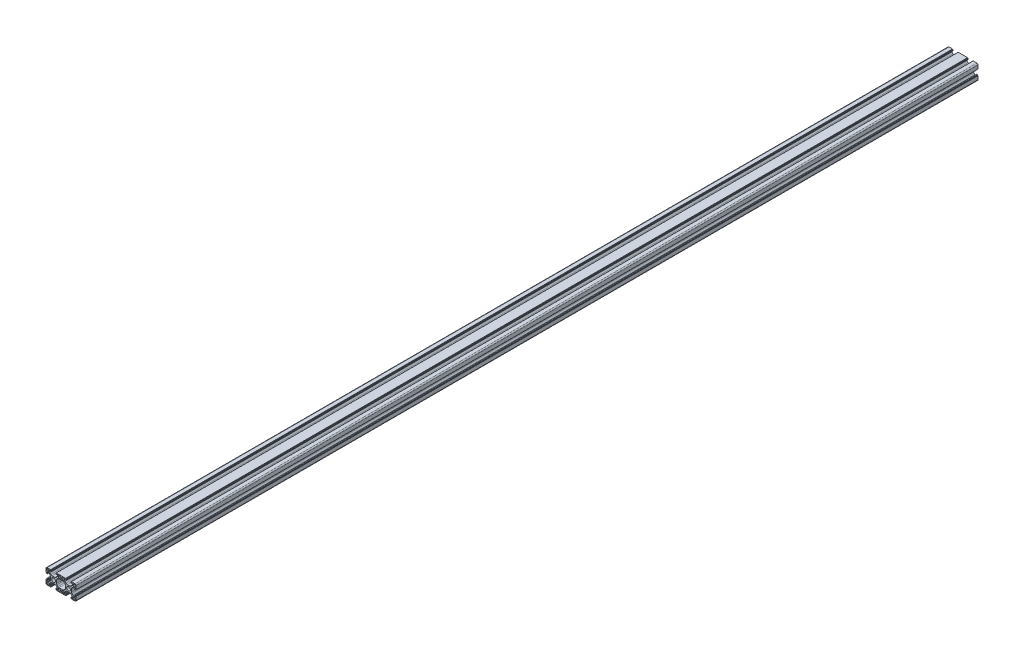
SolidWorks part; units mm, degrees
ref_plane "Спереди" through (0, 0, 0) normal (0, 0, 1) x (1, 0, 0)
ref_plane "Сверху" through (0, 0, 0) normal (0, 1, 0) x (1, 0, 0)
ref_plane "Справа" through (0, 0, 0) normal (1, 0, 0) x (0, 0, -1)
sketch "Эскиз2" plane through (0, 0, 0) normal (0, 0, 1) x (1, 0, 0)
  line L0 (-3.2929, 8.1556) -> (-1.7929, 6.6556) construction
  line L1 (18.2071, 9.6556) -> (15.2071, 6.6556) construction
  line L2 (-10.8929, 0.5556) -> (-0.8929, 10.5556) construction
  line L3 (9.1071, 4.5556) -> (11.0059, 4.5556)
  line L4 (9.1071, 0.5556) -> (19.1071, 10.5556) construction
  line L5 (16.7071, 8.1556) -> (15.2071, 9.6556) construction
  line L6 (12.4201, 5.1414) -> (13.7213, 6.4426)
  line L7 (16.0071, 6.6556) -> (17.4071, 6.6556)
  line L8 (15.2071, 7.4556) -> (15.2071, 8.8556)
  line L9 (17.4071, 9.6556) -> (16.0071, 9.6556)
  line L10 (14.3071, 8.7556) -> (14.3071, 7.8568)
  line L11 (12.8704, 8.6288) -> (13.3507, 9.1091)
  line L12 (12.3071, 10.1047) -> (12.8071, 10.1047)
  line L13 (12.6936, 8.5556) -> (12.4071, 8.5556)
  line L14 (13.7042, 9.2556) -> (13.8071, 9.2556)
  line L15 (12.8071, 10.4056) -> (12.8071, 10.1047)
  line L16 (12.1571, 9.9547) -> (12.1571, 8.8056)
  line L17 (17.6071, 10.5556) -> (12.9571, 10.5556)
  line L18 (18.2071, 8.8556) -> (18.2071, 7.4556)
  line L19 (19.1071, 9.0556) -> (19.1071, 4.4056)
  line L20 (18.5062, 3.6056) -> (17.3571, 3.6056)
  line L21 (18.9571, 4.2556) -> (18.6562, 4.2556)
  line L22 (17.8071, 5.1527) -> (17.8071, 5.2556)
  line L23 (17.1071, 4.142) -> (17.1071, 3.8556)
  line L24 (18.6562, 3.7556) -> (18.6562, 4.2556)
  line L25 (17.1804, 4.3188) -> (17.6607, 4.7991)
  line L26 (17.3071, 5.7556) -> (16.4083, 5.7556)
  line L27 (13.6929, 3.8686) -> (14.9941, 5.1698)
  line L28 (13.1071, 0.5556) -> (13.1071, 2.4544)
  line L29 (13.1071, 0.5556) -> (13.1071, -1.3432)
  line L30 (13.6929, -2.7574) -> (14.9941, -4.0586)
  line L31 (15.2071, -6.3444) -> (15.2071, -7.7444)
  line L32 (16.0071, -5.5444) -> (17.4071, -5.5444)
  line L33 (18.2071, -7.7444) -> (18.2071, -6.3444)
  line L34 (17.3071, -4.6444) -> (16.4083, -4.6444)
  line L35 (17.1804, -3.2076) -> (17.6607, -3.688)
  line L36 (18.6562, -2.6444) -> (18.6562, -3.1444)
  line L37 (17.1071, -3.0309) -> (17.1071, -2.7444)
  line L38 (17.8071, -4.0415) -> (17.8071, -4.1444)
  line L39 (18.9571, -3.1444) -> (18.6562, -3.1444)
  line L40 (18.5062, -2.4944) -> (17.3571, -2.4944)
  line L41 (19.1071, -7.9444) -> (19.1071, -3.2944)
  line L42 (17.4071, -8.5444) -> (16.0071, -8.5444)
  line L43 (17.6071, -9.4444) -> (12.9571, -9.4444)
  line L44 (12.1571, -8.8435) -> (12.1571, -7.6944)
  line L45 (12.8071, -9.2944) -> (12.8071, -8.9935)
  line L46 (13.7042, -8.1444) -> (13.8071, -8.1444)
  line L47 (12.6936, -7.4444) -> (12.4071, -7.4444)
  line L48 (12.3071, -8.9935) -> (12.8071, -8.9935)
  line L49 (12.8704, -7.5176) -> (13.3507, -7.998)
  line L50 (14.3071, -7.6444) -> (14.3071, -6.7456)
  line L51 (12.4201, -4.0302) -> (13.7213, -5.3314)
  line L52 (9.1071, -3.4444) -> (11.0059, -3.4444)
  line L53 (18.2071, -8.5444) -> (15.2071, -5.5444) construction
  line L54 (9.1071, 0.5556) -> (19.1071, -9.4444) construction
  line L55 (16.7071, -7.0444) -> (18.2071, -5.5444) construction
  line L56 (9.1071, -3.4444) -> (7.2083, -3.4444)
  line L57 (5.7941, -4.0302) -> (4.4929, -5.3314)
  line L58 (2.2071, -5.5444) -> (0.8071, -5.5444)
  line L59 (3.0071, -6.3444) -> (3.0071, -7.7444)
  line L60 (0.8071, -8.5444) -> (2.2071, -8.5444)
  line L61 (3.9071, -7.6444) -> (3.9071, -6.7456)
  line L62 (5.3439, -7.5176) -> (4.8636, -7.998)
  line L63 (5.9071, -8.9935) -> (5.4071, -8.9935)
  line L64 (5.5207, -7.4444) -> (5.8071, -7.4444)
  line L65 (4.51, -8.1444) -> (4.4071, -8.1444)
  line L66 (5.4071, -9.2944) -> (5.4071, -8.9935)
  line L67 (6.0571, -8.8435) -> (6.0571, -7.6944)
  line L68 (0.6071, -9.4444) -> (5.2571, -9.4444)
  line L69 (0.0071, -7.7444) -> (0.0071, -6.3444)
  line L70 (0.9071, -4.6444) -> (1.8059, -4.6444)
  line L71 (4.5213, -2.7574) -> (3.2201, -4.0586)
  line L72 (5.1071, 0.5556) -> (5.1071, -1.3432)
  line L73 (-1.7929, 9.6556) -> (-4.7929, 6.6556) construction
  line L74 (0.0071, -8.5444) -> (3.0071, -5.5444) construction
  line L75 (-3.2929, -7.0444) -> (-4.7929, -8.5444) construction
  line L76 (9.1071, 0.5556) -> (-0.8929, -9.4444) construction
  line L77 (1.5071, -7.0444) -> (3.0071, -8.5444) construction
  line L78 (5.1071, 0.5556) -> (5.1071, 2.4544)
  line L79 (4.5213, 3.8686) -> (3.2201, 5.1698)
  line L80 (3.0071, 7.4556) -> (3.0071, 8.8556)
  line L81 (2.2071, 6.6556) -> (0.8071, 6.6556)
  line L82 (0.0071, 8.8556) -> (0.0071, 7.4556)
  line L83 (0.9071, 5.7556) -> (1.8059, 5.7556)
  line L84 (0.8071, 9.6556) -> (2.2071, 9.6556)
  line L85 (0.6071, 10.5556) -> (5.2571, 10.5556)
  line L86 (6.0571, 9.9547) -> (6.0571, 8.8056)
  line L87 (5.4071, 10.4056) -> (5.4071, 10.1047)
  line L88 (4.51, 9.2556) -> (4.4071, 9.2556)
  line L89 (5.5207, 8.5556) -> (5.8071, 8.5556)
  line L90 (5.9071, 10.1047) -> (5.4071, 10.1047)
  line L91 (5.3439, 8.6288) -> (4.8636, 9.1091)
  line L92 (3.9071, 8.7556) -> (3.9071, 7.8568)
  line L93 (5.7941, 5.1414) -> (4.4929, 6.4426)
  line L94 (9.1071, 4.5556) -> (7.2083, 4.5556)
  line L95 (-2.6569, 0.5556) -> (20.6115, 0.5556) construction
  line L96 (0.0071, 9.6556) -> (3.0071, 6.6556) construction
  line L97 (9.1071, -11.5308) -> (9.1071, 11.2745) construction
  line L98 (9.1071, 0.5556) -> (-0.8929, 10.5556) construction
  line L99 (1.5071, 8.1556) -> (0.0071, 6.6556) construction
  line L100 (-10.8929, 0.5556) -> (-0.8929, -9.4444) construction
  line L101 (-1.7929, -8.5444) -> (-4.7929, -5.5444) construction
  line L102 (-18.4929, -7.0444) -> (-19.9929, -5.5444) construction
  line L103 (-10.8929, 0.5556) -> (-20.8929, -9.4444) construction
  line L104 (-19.9929, -8.5444) -> (-16.9929, -5.5444) construction
  line L105 (-18.4929, 8.1556) -> (-16.9929, 9.6556) construction
  line L106 (-10.8929, 0.5556) -> (-20.8929, 10.5556) construction
  line L107 (-19.9929, 9.6556) -> (-16.9929, 6.6556) construction
  line L108 (-10.8929, 4.5556) -> (-8.9941, 4.5556)
  line L109 (-7.5799, 5.1414) -> (-6.2787, 6.4426)
  line L110 (-5.6929, 8.7556) -> (-5.6929, 7.8568)
  line L111 (-7.1296, 8.6288) -> (-6.6493, 9.1091)
  line L112 (-7.6929, 10.1047) -> (-7.1929, 10.1047)
  line L113 (-7.3064, 8.5556) -> (-7.5929, 8.5556)
  line L114 (-6.2958, 9.2556) -> (-6.1929, 9.2556)
  line L115 (-7.1929, 10.4056) -> (-7.1929, 10.1047)
  line L116 (-7.8429, 9.9547) -> (-7.8429, 8.8056)
  line L117 (-2.3929, 10.5556) -> (-7.0429, 10.5556)
  line L118 (-2.5929, 9.6556) -> (-3.9929, 9.6556)
  line L119 (-2.6929, 5.7556) -> (-3.5917, 5.7556)
  line L120 (-1.7929, 8.8556) -> (-1.7929, 7.4556)
  line L121 (-3.9929, 6.6556) -> (-2.5929, 6.6556)
  line L122 (-4.7929, 7.4556) -> (-4.7929, 8.8556)
  line L123 (-6.3071, 3.8686) -> (-5.0059, 5.1698)
  line L124 (-6.8929, 0.5556) -> (-6.8929, 2.4544)
  line L125 (-6.8929, 0.5556) -> (-6.8929, -1.3432)
  line L126 (-6.3071, -2.7574) -> (-5.0059, -4.0586)
  line L127 (-2.6929, -4.6444) -> (-3.5917, -4.6444)
  line L128 (-1.7929, -7.7444) -> (-1.7929, -6.3444)
  line L129 (-2.3929, -9.4444) -> (-7.0429, -9.4444)
  line L130 (-7.8429, -8.8435) -> (-7.8429, -7.6944)
  line L131 (-7.1929, -9.2944) -> (-7.1929, -8.9935)
  line L132 (-6.2958, -8.1444) -> (-6.1929, -8.1444)
  line L133 (-7.3064, -7.4444) -> (-7.5929, -7.4444)
  line L134 (-7.6929, -8.9935) -> (-7.1929, -8.9935)
  line L135 (-7.1296, -7.5176) -> (-6.6493, -7.998)
  line L136 (-5.6929, -7.6444) -> (-5.6929, -6.7456)
  line L137 (-2.5929, -8.5444) -> (-3.9929, -8.5444)
  line L138 (-4.7929, -6.3444) -> (-4.7929, -7.7444)
  line L139 (-3.9929, -5.5444) -> (-2.5929, -5.5444)
  line L140 (-7.5799, -4.0302) -> (-6.2787, -5.3314)
  line L141 (-10.8929, -3.4444) -> (-8.9941, -3.4444)
  line L142 (-10.8929, -3.4444) -> (-12.7917, -3.4444)
  line L143 (-14.2059, -4.0302) -> (-15.5071, -5.3314)
  line L144 (-16.0929, -7.6444) -> (-16.0929, -6.7456)
  line L145 (-14.6561, -7.5176) -> (-15.1364, -7.998)
  line L146 (-14.0929, -8.9935) -> (-14.5929, -8.9935)
  line L147 (-14.4793, -7.4444) -> (-14.1929, -7.4444)
  line L148 (-15.49, -8.1444) -> (-15.5929, -8.1444)
  line L149 (-14.5929, -9.2944) -> (-14.5929, -8.9935)
  line L150 (-13.9429, -8.8435) -> (-13.9429, -7.6944)
  line L151 (-19.3929, -9.4444) -> (-14.7429, -9.4444)
  line L152 (-19.1929, -8.5444) -> (-17.7929, -8.5444)
  line L153 (-20.8929, -7.9444) -> (-20.8929, -3.2944)
  line L154 (-20.2919, -2.4944) -> (-19.1429, -2.4944)
  line L155 (-20.7429, -3.1444) -> (-20.4419, -3.1444)
  line L156 (-19.5929, -4.0415) -> (-19.5929, -4.1444)
  line L157 (-18.8929, -3.0309) -> (-18.8929, -2.7444)
  line L158 (-20.4419, -2.6444) -> (-20.4419, -3.1444)
  line L159 (-18.9661, -3.2076) -> (-19.4464, -3.688)
  line L160 (-19.0929, -4.6444) -> (-18.1941, -4.6444)
  line L161 (-19.9929, -7.7444) -> (-19.9929, -6.3444)
  line L162 (-17.7929, -5.5444) -> (-19.1929, -5.5444)
  line L163 (-16.9929, -6.3444) -> (-16.9929, -7.7444)
  line L164 (-15.4787, -2.7574) -> (-16.7799, -4.0586)
  line L165 (-14.8929, 0.5556) -> (-14.8929, -1.3432)
  line L166 (-14.8929, 0.5556) -> (-14.8929, 2.4544)
  line L167 (-15.4787, 3.8686) -> (-16.7799, 5.1698)
  line L168 (-19.0929, 5.7556) -> (-18.1941, 5.7556)
  line L169 (-18.9661, 4.3188) -> (-19.4464, 4.7991)
  line L170 (-20.4419, 3.7556) -> (-20.4419, 4.2556)
  line L171 (-18.8929, 4.142) -> (-18.8929, 3.8556)
  line L172 (-19.5929, 5.1527) -> (-19.5929, 5.2556)
  line L173 (-20.7429, 4.2556) -> (-20.4419, 4.2556)
  line L174 (-20.2919, 3.6056) -> (-19.1429, 3.6056)
  line L175 (-20.8929, 9.0556) -> (-20.8929, 4.4056)
  line L176 (-19.9929, 8.8556) -> (-19.9929, 7.4556)
  line L177 (-19.3929, 10.5556) -> (-14.7429, 10.5556)
  line L178 (-13.9429, 9.9547) -> (-13.9429, 8.8056)
  line L179 (-14.5929, 10.4056) -> (-14.5929, 10.1047)
  line L180 (-15.49, 9.2556) -> (-15.5929, 9.2556)
  line L181 (-14.4793, 8.5556) -> (-14.1929, 8.5556)
  line L182 (-14.0929, 10.1047) -> (-14.5929, 10.1047)
  line L183 (-14.6561, 8.6288) -> (-15.1364, 9.1091)
  line L184 (-16.0929, 8.7556) -> (-16.0929, 7.8568)
  line L185 (-19.1929, 9.6556) -> (-17.7929, 9.6556)
  line L186 (-16.9929, 7.4556) -> (-16.9929, 8.8556)
  line L187 (-17.7929, 6.6556) -> (-19.1929, 6.6556)
  line L188 (-14.2059, 5.1414) -> (-15.5071, 6.4426)
  line L189 (-10.8929, 4.5556) -> (-12.7917, 4.5556)
  line L190 (-2.3929, -9.4444) -> (0.6071, -9.4444)
  line L191 (-2.6929, -4.6444) -> (0.9071, -4.6444)
  line L192 (-2.6929, 5.7556) -> (0.9071, 5.7556)
  line L193 (-2.3929, 10.5556) -> (0.6071, 10.5556)
  arc A0 (18.2071, 8.8556) -> (17.4071, 9.6556) centre (17.4071, 8.8556) ccw
  arc A1 (16.0071, 9.6556) -> (15.2071, 8.8556) centre (16.0071, 8.8556) ccw
  arc A2 (16.0071, 6.6556) -> (15.2071, 7.4556) centre (16.0071, 7.4556) cw
  arc A3 (17.6071, 10.5556) -> (19.1071, 9.0556) centre (17.6071, 9.0556) cw
  arc A4 (12.3071, 10.1047) -> (12.1571, 9.9547) centre (12.3071, 9.9547) ccw
  arc A5 (12.9571, 10.5556) -> (12.8071, 10.4056) centre (12.9571, 10.4056) ccw
  arc A6 (12.6936, 8.5556) -> (12.8704, 8.6288) centre (12.6936, 8.8056) ccw
  arc A7 (12.4071, 8.5556) -> (12.1571, 8.8056) centre (12.4071, 8.8056) cw
  arc A8 (13.3507, 9.1091) -> (13.7042, 9.2556) centre (13.7042, 8.7556) cw
  arc A9 (13.8071, 9.2556) -> (14.3071, 8.7556) centre (13.8071, 8.7556) cw
  arc A10 (11.6071, 0.5556) -> (9.1071, 3.0556) centre (9.1071, 0.5556) ccw
  arc A11 (11.0059, 4.5556) -> (12.4201, 5.1414) centre (11.0059, 6.5556) ccw
  arc A12 (14.3071, 7.8568) -> (13.7213, 6.4426) centre (12.3071, 7.8568) cw
  arc A13 (18.2071, 7.4556) -> (17.4071, 6.6556) centre (17.4071, 7.4556) cw
  arc A14 (17.8071, 5.2556) -> (17.3071, 5.7556) centre (17.3071, 5.2556) ccw
  arc A15 (17.6607, 4.7991) -> (17.8071, 5.1527) centre (17.3071, 5.1527) ccw
  arc A16 (17.1071, 3.8556) -> (17.3571, 3.6056) centre (17.3571, 3.8556) ccw
  arc A17 (17.1071, 4.142) -> (17.1804, 4.3188) centre (17.3571, 4.142) cw
  arc A18 (19.1071, 4.4056) -> (18.9571, 4.2556) centre (18.9571, 4.4056) cw
  arc A19 (18.6562, 3.7556) -> (18.5062, 3.6056) centre (18.5062, 3.7556) cw
  arc A20 (16.4083, 5.7556) -> (14.9941, 5.1698) centre (16.4083, 3.7556) ccw
  arc A21 (13.1071, 2.4544) -> (13.6929, 3.8686) centre (15.1071, 2.4544) cw
  arc A22 (17.4071, -8.5444) -> (18.2071, -7.7444) centre (17.4071, -7.7444) ccw
  arc A23 (18.2071, -6.3444) -> (17.4071, -5.5444) centre (17.4071, -6.3444) ccw
  arc A24 (15.2071, -6.3444) -> (16.0071, -5.5444) centre (16.0071, -6.3444) cw
  arc A25 (19.1071, -7.9444) -> (17.6071, -9.4444) centre (17.6071, -7.9444) cw
  arc A26 (18.6562, -2.6444) -> (18.5062, -2.4944) centre (18.5062, -2.6444) ccw
  arc A27 (19.1071, -3.2944) -> (18.9571, -3.1444) centre (18.9571, -3.2944) ccw
  arc A28 (17.1071, -3.0309) -> (17.1804, -3.2076) centre (17.3571, -3.0309) ccw
  arc A29 (17.1071, -2.7444) -> (17.3571, -2.4944) centre (17.3571, -2.7444) cw
  arc A30 (17.6607, -3.688) -> (17.8071, -4.0415) centre (17.3071, -4.0415) cw
  arc A31 (17.8071, -4.1444) -> (17.3071, -4.6444) centre (17.3071, -4.1444) cw
  arc A32 (9.1071, -1.9444) -> (11.6071, 0.5556) centre (9.1071, 0.5556) ccw
  arc A33 (13.1071, -1.3432) -> (13.6929, -2.7574) centre (15.1071, -1.3432) ccw
  arc A34 (16.4083, -4.6444) -> (14.9941, -4.0586) centre (16.4083, -2.6444) cw
  arc A35 (16.0071, -8.5444) -> (15.2071, -7.7444) centre (16.0071, -7.7444) cw
  arc A36 (13.8071, -8.1444) -> (14.3071, -7.6444) centre (13.8071, -7.6444) ccw
  arc A37 (13.3507, -7.998) -> (13.7042, -8.1444) centre (13.7042, -7.6444) ccw
  arc A38 (12.4071, -7.4444) -> (12.1571, -7.6944) centre (12.4071, -7.6944) ccw
  arc A39 (12.6936, -7.4444) -> (12.8704, -7.5176) centre (12.6936, -7.6944) cw
  arc A40 (12.9571, -9.4444) -> (12.8071, -9.2944) centre (12.9571, -9.2944) cw
  arc A41 (12.3071, -8.9935) -> (12.1571, -8.8435) centre (12.3071, -8.8435) cw
  arc A42 (14.3071, -6.7456) -> (13.7213, -5.3314) centre (12.3071, -6.7456) ccw
  arc A43 (11.0059, -3.4444) -> (12.4201, -4.0302) centre (11.0059, -5.4444) cw
  arc A44 (0.0071, -7.7444) -> (0.8071, -8.5444) centre (0.8071, -7.7444) ccw
  arc A45 (2.2071, -8.5444) -> (3.0071, -7.7444) centre (2.2071, -7.7444) ccw
  arc A46 (2.2071, -5.5444) -> (3.0071, -6.3444) centre (2.2071, -6.3444) cw
  arc A47 (5.9071, -8.9935) -> (6.0571, -8.8435) centre (5.9071, -8.8435) ccw
  arc A48 (5.2571, -9.4444) -> (5.4071, -9.2944) centre (5.2571, -9.2944) ccw
  arc A49 (5.5207, -7.4444) -> (5.3439, -7.5176) centre (5.5207, -7.6944) ccw
  arc A50 (5.8071, -7.4444) -> (6.0571, -7.6944) centre (5.8071, -7.6944) cw
  arc A51 (4.8636, -7.998) -> (4.51, -8.1444) centre (4.51, -7.6444) cw
  arc A52 (4.4071, -8.1444) -> (3.9071, -7.6444) centre (4.4071, -7.6444) cw
  arc A53 (6.6071, 0.5556) -> (9.1071, -1.9444) centre (9.1071, 0.5556) ccw
  arc A54 (7.2083, -3.4444) -> (5.7941, -4.0302) centre (7.2083, -5.4444) ccw
  arc A55 (3.9071, -6.7456) -> (4.4929, -5.3314) centre (5.9071, -6.7456) cw
  arc A56 (0.0071, -6.3444) -> (0.8071, -5.5444) centre (0.8071, -6.3444) cw
  arc A57 (1.8059, -4.6444) -> (3.2201, -4.0586) centre (1.8059, -2.6444) ccw
  arc A58 (5.1071, -1.3432) -> (4.5213, -2.7574) centre (3.1071, -1.3432) cw
  arc A59 (0.8071, 9.6556) -> (0.0071, 8.8556) centre (0.8071, 8.8556) ccw
  arc A60 (0.0071, 7.4556) -> (0.8071, 6.6556) centre (0.8071, 7.4556) ccw
  arc A61 (3.0071, 7.4556) -> (2.2071, 6.6556) centre (2.2071, 7.4556) cw
  arc A62 (9.1071, 3.0556) -> (6.6071, 0.5556) centre (9.1071, 0.5556) ccw
  arc A63 (5.1071, 2.4544) -> (4.5213, 3.8686) centre (3.1071, 2.4544) ccw
  arc A64 (1.8059, 5.7556) -> (3.2201, 5.1698) centre (1.8059, 3.7556) cw
  arc A65 (2.2071, 9.6556) -> (3.0071, 8.8556) centre (2.2071, 8.8556) cw
  arc A66 (4.4071, 9.2556) -> (3.9071, 8.7556) centre (4.4071, 8.7556) ccw
  arc A67 (4.8636, 9.1091) -> (4.51, 9.2556) centre (4.51, 8.7556) ccw
  arc A68 (5.8071, 8.5556) -> (6.0571, 8.8056) centre (5.8071, 8.8056) ccw
  arc A69 (5.5207, 8.5556) -> (5.3439, 8.6288) centre (5.5207, 8.8056) cw
  arc A70 (5.2571, 10.5556) -> (5.4071, 10.4056) centre (5.2571, 10.4056) cw
  arc A71 (5.9071, 10.1047) -> (6.0571, 9.9547) centre (5.9071, 9.9547) cw
  arc A72 (3.9071, 7.8568) -> (4.4929, 6.4426) centre (5.9071, 7.8568) ccw
  arc A73 (7.2083, 4.5556) -> (5.7941, 5.1414) centre (7.2083, 6.5556) cw
  arc A74 (-8.9941, 4.5556) -> (-7.5799, 5.1414) centre (-8.9941, 6.5556) ccw
  arc A75 (-5.6929, 7.8568) -> (-6.2787, 6.4426) centre (-7.6929, 7.8568) cw
  arc A76 (-7.6929, 10.1047) -> (-7.8429, 9.9547) centre (-7.6929, 9.9547) ccw
  arc A77 (-7.0429, 10.5556) -> (-7.1929, 10.4056) centre (-7.0429, 10.4056) ccw
  arc A78 (-7.3064, 8.5556) -> (-7.1296, 8.6288) centre (-7.3064, 8.8056) ccw
  arc A79 (-7.5929, 8.5556) -> (-7.8429, 8.8056) centre (-7.5929, 8.8056) cw
  arc A80 (-6.6493, 9.1091) -> (-6.2958, 9.2556) centre (-6.2958, 8.7556) cw
  arc A81 (-6.1929, 9.2556) -> (-5.6929, 8.7556) centre (-6.1929, 8.7556) cw
  arc A82 (-3.9929, 9.6556) -> (-4.7929, 8.8556) centre (-3.9929, 8.8556) ccw
  arc A83 (-3.5917, 5.7556) -> (-5.0059, 5.1698) centre (-3.5917, 3.7556) ccw
  arc A84 (-6.8929, 2.4544) -> (-6.3071, 3.8686) centre (-4.8929, 2.4544) cw
  arc A85 (-10.8929, 3.0556) -> (-8.3929, 0.5556) centre (-10.8929, 0.5556) cw
  arc A86 (-4.7929, 7.4556) -> (-3.9929, 6.6556) centre (-3.9929, 7.4556) ccw
  arc A87 (-1.7929, 7.4556) -> (-2.5929, 6.6556) centre (-2.5929, 7.4556) cw
  arc A88 (-2.5929, 9.6556) -> (-1.7929, 8.8556) centre (-2.5929, 8.8556) cw
  arc A89 (-6.8929, -1.3432) -> (-6.3071, -2.7574) centre (-4.8929, -1.3432) ccw
  arc A90 (-3.5917, -4.6444) -> (-5.0059, -4.0586) centre (-3.5917, -2.6444) cw
  arc A91 (-1.7929, -6.3444) -> (-2.5929, -5.5444) centre (-2.5929, -6.3444) ccw
  arc A92 (-5.6929, -6.7456) -> (-6.2787, -5.3314) centre (-7.6929, -6.7456) ccw
  arc A93 (-8.9941, -3.4444) -> (-7.5799, -4.0302) centre (-8.9941, -5.4444) cw
  arc A94 (-8.3929, 0.5556) -> (-10.8929, -1.9444) centre (-10.8929, 0.5556) cw
  arc A95 (-6.1929, -8.1444) -> (-5.6929, -7.6444) centre (-6.1929, -7.6444) ccw
  arc A96 (-6.6493, -7.998) -> (-6.2958, -8.1444) centre (-6.2958, -7.6444) ccw
  arc A97 (-7.5929, -7.4444) -> (-7.8429, -7.6944) centre (-7.5929, -7.6944) ccw
  arc A98 (-7.3064, -7.4444) -> (-7.1296, -7.5176) centre (-7.3064, -7.6944) cw
  arc A99 (-7.0429, -9.4444) -> (-7.1929, -9.2944) centre (-7.0429, -9.2944) cw
  arc A100 (-7.6929, -8.9935) -> (-7.8429, -8.8435) centre (-7.6929, -8.8435) cw
  arc A101 (-3.9929, -5.5444) -> (-4.7929, -6.3444) centre (-3.9929, -6.3444) ccw
  arc A102 (-3.9929, -8.5444) -> (-4.7929, -7.7444) centre (-3.9929, -7.7444) cw
  arc A103 (-1.7929, -7.7444) -> (-2.5929, -8.5444) centre (-2.5929, -7.7444) cw
  arc A104 (-12.7917, -3.4444) -> (-14.2059, -4.0302) centre (-12.7917, -5.4444) ccw
  arc A105 (-16.0929, -6.7456) -> (-15.5071, -5.3314) centre (-14.0929, -6.7456) cw
  arc A106 (-14.0929, -8.9935) -> (-13.9429, -8.8435) centre (-14.0929, -8.8435) ccw
  arc A107 (-14.7429, -9.4444) -> (-14.5929, -9.2944) centre (-14.7429, -9.2944) ccw
  arc A108 (-14.4793, -7.4444) -> (-14.6561, -7.5176) centre (-14.4793, -7.6944) ccw
  arc A109 (-14.1929, -7.4444) -> (-13.9429, -7.6944) centre (-14.1929, -7.6944) cw
  arc A110 (-15.1364, -7.998) -> (-15.49, -8.1444) centre (-15.49, -7.6444) cw
  arc A111 (-15.5929, -8.1444) -> (-16.0929, -7.6444) centre (-15.5929, -7.6444) cw
  arc A112 (-17.7929, -8.5444) -> (-16.9929, -7.7444) centre (-17.7929, -7.7444) ccw
  arc A113 (-18.1941, -4.6444) -> (-16.7799, -4.0586) centre (-18.1941, -2.6444) ccw
  arc A114 (-14.8929, -1.3432) -> (-15.4787, -2.7574) centre (-16.8929, -1.3432) cw
  arc A115 (-10.8929, -1.9444) -> (-13.3929, 0.5556) centre (-10.8929, 0.5556) cw
  arc A116 (-19.5929, -4.1444) -> (-19.0929, -4.6444) centre (-19.0929, -4.1444) ccw
  arc A117 (-19.4464, -3.688) -> (-19.5929, -4.0415) centre (-19.0929, -4.0415) ccw
  arc A118 (-18.8929, -2.7444) -> (-19.1429, -2.4944) centre (-19.1429, -2.7444) ccw
  arc A119 (-18.8929, -3.0309) -> (-18.9661, -3.2076) centre (-19.1429, -3.0309) cw
  arc A120 (-20.8929, -3.2944) -> (-20.7429, -3.1444) centre (-20.7429, -3.2944) cw
  arc A121 (-20.4419, -2.6444) -> (-20.2919, -2.4944) centre (-20.2919, -2.6444) cw
  arc A122 (-20.8929, -7.9444) -> (-19.3929, -9.4444) centre (-19.3929, -7.9444) ccw
  arc A123 (-16.9929, -6.3444) -> (-17.7929, -5.5444) centre (-17.7929, -6.3444) ccw
  arc A124 (-19.9929, -6.3444) -> (-19.1929, -5.5444) centre (-19.1929, -6.3444) cw
  arc A125 (-19.1929, -8.5444) -> (-19.9929, -7.7444) centre (-19.1929, -7.7444) cw
  arc A126 (-14.8929, 2.4544) -> (-15.4787, 3.8686) centre (-16.8929, 2.4544) ccw
  arc A127 (-18.1941, 5.7556) -> (-16.7799, 5.1698) centre (-18.1941, 3.7556) cw
  arc A128 (-20.4419, 3.7556) -> (-20.2919, 3.6056) centre (-20.2919, 3.7556) ccw
  arc A129 (-20.8929, 4.4056) -> (-20.7429, 4.2556) centre (-20.7429, 4.4056) ccw
  arc A130 (-18.8929, 4.142) -> (-18.9661, 4.3188) centre (-19.1429, 4.142) ccw
  arc A131 (-18.8929, 3.8556) -> (-19.1429, 3.6056) centre (-19.1429, 3.8556) cw
  arc A132 (-19.4464, 4.7991) -> (-19.5929, 5.1527) centre (-19.0929, 5.1527) cw
  arc A133 (-19.5929, 5.2556) -> (-19.0929, 5.7556) centre (-19.0929, 5.2556) cw
  arc A134 (-19.9929, 7.4556) -> (-19.1929, 6.6556) centre (-19.1929, 7.4556) ccw
  arc A135 (-16.0929, 7.8568) -> (-15.5071, 6.4426) centre (-14.0929, 7.8568) ccw
  arc A136 (-12.7917, 4.5556) -> (-14.2059, 5.1414) centre (-12.7917, 6.5556) cw
  arc A137 (-13.3929, 0.5556) -> (-10.8929, 3.0556) centre (-10.8929, 0.5556) cw
  arc A138 (-15.5929, 9.2556) -> (-16.0929, 8.7556) centre (-15.5929, 8.7556) ccw
  arc A139 (-15.1364, 9.1091) -> (-15.49, 9.2556) centre (-15.49, 8.7556) ccw
  arc A140 (-14.1929, 8.5556) -> (-13.9429, 8.8056) centre (-14.1929, 8.8056) ccw
  arc A141 (-14.4793, 8.5556) -> (-14.6561, 8.6288) centre (-14.4793, 8.8056) cw
  arc A142 (-14.7429, 10.5556) -> (-14.5929, 10.4056) centre (-14.7429, 10.4056) cw
  arc A143 (-14.0929, 10.1047) -> (-13.9429, 9.9547) centre (-14.0929, 9.9547) cw
  arc A144 (-19.3929, 10.5556) -> (-20.8929, 9.0556) centre (-19.3929, 9.0556) ccw
  arc A145 (-17.7929, 6.6556) -> (-16.9929, 7.4556) centre (-17.7929, 7.4556) ccw
  arc A146 (-17.7929, 9.6556) -> (-16.9929, 8.8556) centre (-17.7929, 8.8556) cw
  arc A147 (-19.9929, 8.8556) -> (-19.1929, 9.6556) centre (-19.1929, 8.8556) cw
  point P0 (9.1071, 0.5556)
  point P12 (9.1071, 0.5556)
  point P45 (17.8071, 4.2556)
  point P104 (12.8071, -8.1444)
  point P155 (12.8071, 9.2556)
  point P163 (17.8071, -3.1444)
  point P164 (9.1071, -3.3687)
  point P166 (9.1071, 0.5556)
  point P224 (5.4071, -8.1444)
  point P225 (5.1829, 0.5556)
  point P227 (9.1071, 0.5556)
  point P267 (5.4071, 9.2556)
  point P272 (13.0314, 0.5556)
  point P288 (9.1071, 4.4799)
  point P290 (9.1071, 0.5556)
  point P515 (-10.8929, 4.4799)
  point P516 (-14.8171, 0.5556)
  point P517 (-7.1929, 9.2556)
  point P518 (-6.9686, 0.5556)
  point P519 (-7.1929, -8.1444)
  point P520 (-10.8929, -3.3687)
  point P521 (-19.5929, -3.1444)
  point P522 (-14.5929, 9.2556)
  point P523 (-14.5929, -8.1444)
  point P524 (-19.5929, 4.2556)
  dimension "D3" = 5
  dimension "D6" = 2
  dimension "D1" = 2
  dimension "D2" = 6
  dimension "D4" = 4
  dimension "D5" = 0.9
extrude "Бобышка-Вытянуть1" add sketch "Эскиз2" along normal blind 1200
